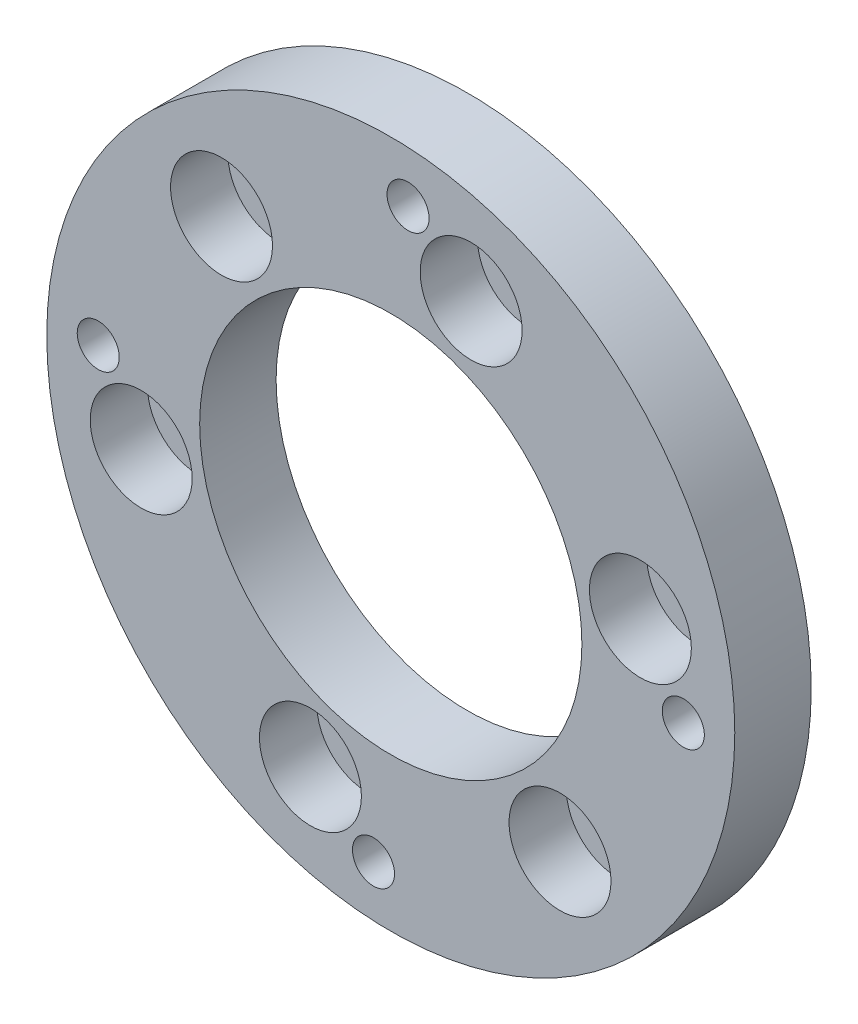
SolidWorks part; units mm, degrees
ref_plane "Plan1" through (0, 0, 0) normal (0, 0, 1) x (1, 0, 0)
ref_plane "Plan2" through (0, 0, 0) normal (0, 1, 0) x (1, 0, 0)
ref_plane "Plan3" through (0, 0, 0) normal (1, 0, 0) x (0, 0, -1)
sketch "Esquisse5" plane through (0, 0, 0) normal (0, 0, 1) x (1, 0, 0)
  circle A0 centre (0, 0) radius 27
  circle A1 centre (0, 0) radius 15
  dimension "D1" = 30
  dimension "D2" = 54
extrude "Base-Extrusion" add sketch "Esquisse5" along normal blind 6
sketch "Esquisse9" plane through (0, 0, 0) normal (0, 0, -1) x (-1, 0, 0)
  circle A0 centre (22.96, 1.3561) radius 2.15 construction
  point P0 (22.96, 1.3561)
hole_wizard "Trou taraudé M4x0.71" positions "Esquisse11" profile "Esquisse10" tap size "M4x0.7" standard "ISO"
sketch "Esquisse11" plane through (0, 0, 0) normal (0, 0, -1) x (-1, 0, 0)
  point P0 (22.96, 1.3561)
cosmetic thread "Représentation de filetage1" parameters "D2"=4
sketch "Esquisse10" plane through (-22.96, 1.3561, 0) normal (1, 0, 0) x (0, 1, 0)
  line L0 (0, 0) -> (0, 6)
  line L1 (0, 6) -> (1.65, 6)
  line L2 (1.65, 6) -> (1.65, 0)
  line L5 (1.65, 0) -> (0, 0)
  line L11 (0, -6.35) -> (0, 107.95) construction
  dimension "Diamètre du trou pour taraudage jusqu'au prochain" = 3.3
  dimension "Profondeur du trou pour taraudage jusqu'au prochain" = 6
pattern_circular "Répétition circulaire1" count 4 every 90
sketch "Esquisse12" plane through (0, 0, 6) normal (0, 0, 1) x (1, 0, 0)
  point P0 (-13.2837, 14.9513)
hole_wizard "Chambrage pour vis à tête cylindrique à 6 pans creux (vis CHC) M41" positions "Esquisse16" profile "Esquisse15" counterbore size "M4" standard "ISO"
sketch "Esquisse16" plane through (0, 0, 6) normal (0, 0, 1) x (1, 0, 0)
  point P0 (-13.2837, 14.9513)
sketch "Esquisse15" plane through (-13.2837, 14.9513, 6) normal (1, 0, 0) x (0, -1, 0)
  line L0 (0, 0) -> (0, 6)
  line L1 (0, 6) -> (2.25, 6)
  line L3 (2.25, 6) -> (2.25, 4.5)
  line L4 (2.25, 4.5) -> (4, 4.5)
  line L5 (4, 4.5) -> (4, 0)
  line L7 (4, 0) -> (0, 0)
  line L11 (0, -6.35) -> (0, 107.95) construction
  dimension "Diamètre du perçage jusqu'au prochain" = 4.5
  dimension "Profondeur du perçage jusqu'au prochain" = 6
  dimension "Diamètre du chambrage" = 8
  dimension "Profondeur du chambrage" = 4.5
pattern_circular "Répétition circulaire2" count 6 over 360
